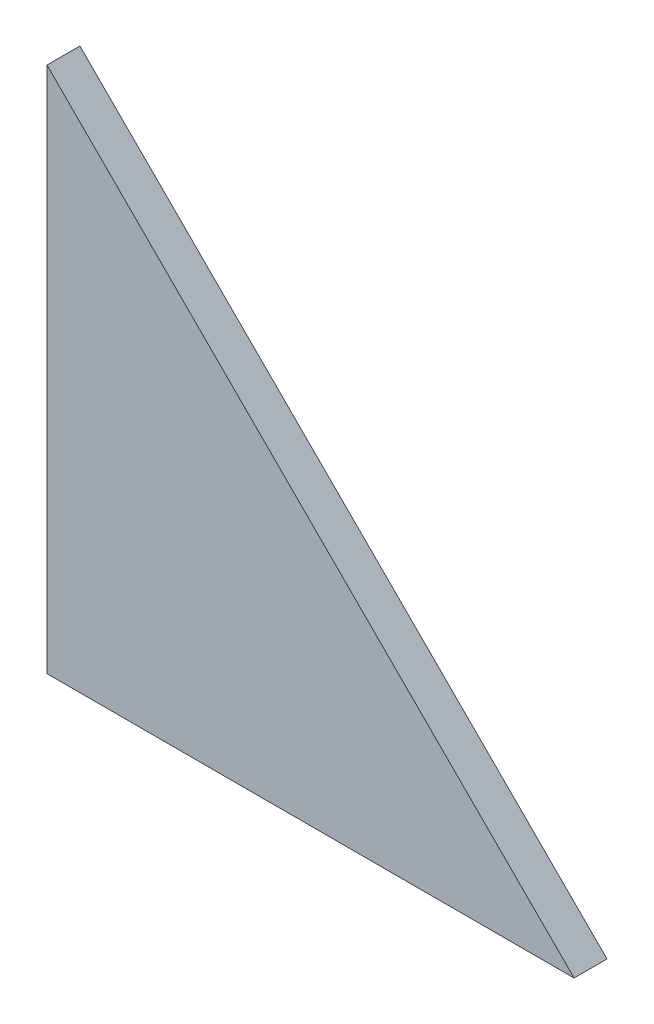
SolidWorks part; units mm, degrees
material "Pine"
ref_plane "Front Plane" through (0, 0, 0) normal (0, 0, 1) x (1, 0, 0)
ref_plane "Top Plane" through (0, 0, 0) normal (0, 1, 0) x (1, 0, 0)
ref_plane "Right Plane" through (0, 0, 0) normal (1, 0, 0) x (0, 0, -1)
sketch "Sketch1" plane through (0, 0, 0) normal (0, 0, 1) x (1, 0, 0)
  line L0 (0, 0) -> (304.8, 0)
  line L1 (304.8, 0) -> (0, 304.8)
  line L2 (0, 304.8) -> (0, 0)
  dimension "D1" = 304.8
extrude "Boss-Extrude1" add sketch "Sketch1" along normal mid plane 19.05 contours L1 L2 L0
